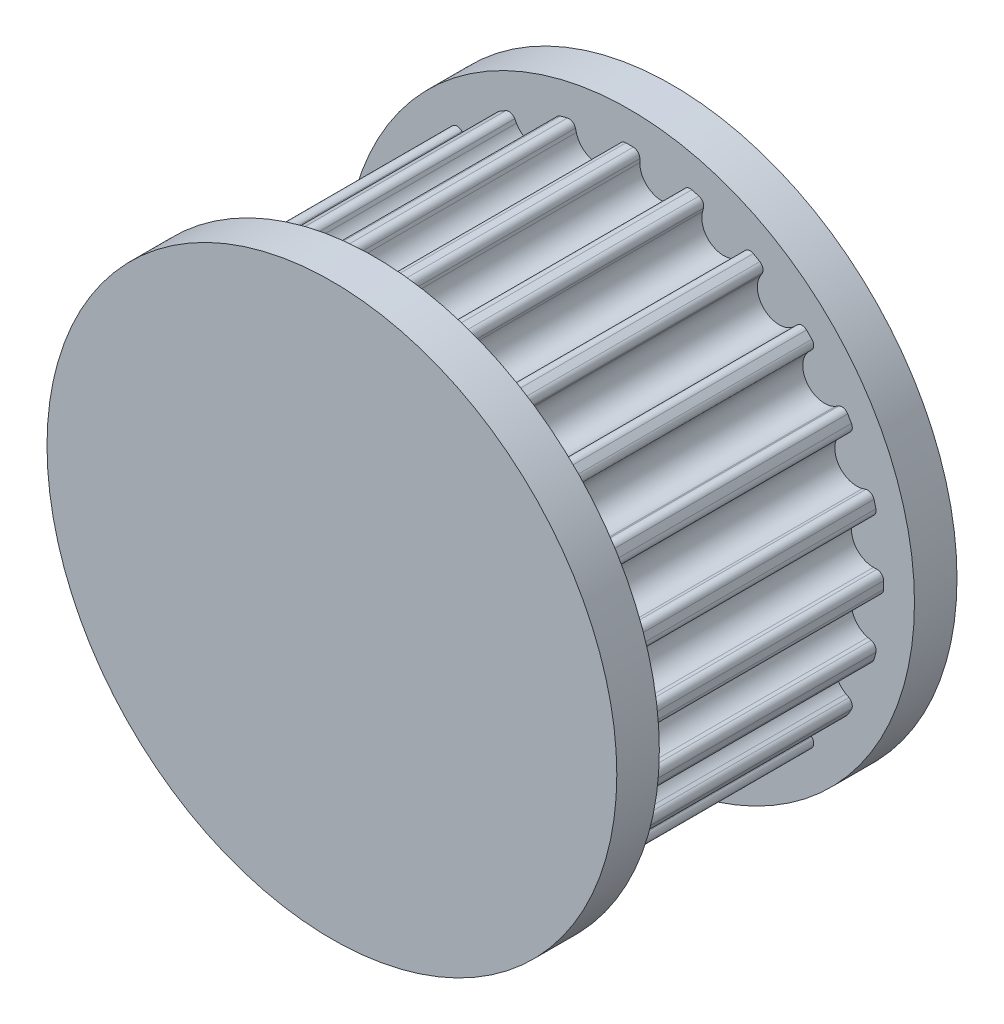
SolidWorks part; units mm, degrees
ref_plane "前视基准面" through (0, 0, 0) normal (0, 0, 1) x (1, 0, 0)
ref_plane "上视基准面" through (0, 0, 0) normal (0, 1, 0) x (1, 0, 0)
ref_plane "右视基准面" through (0, 0, 0) normal (1, 0, 0) x (0, 0, -1)
sketch "Sketch2" plane through (0, 0, 0) normal (0, 0, 1) x (1, 0, 0)
  circle A0 centre (0, 0) radius 29.875
  dimension "D1" = 59.75
extrude "Extrude1" add sketch "Sketch2" along normal blind 30
sketch "Sketch1" plane through (0, 0, 0) normal (0, 0, 1) x (1, 0, 0)
  line L0 (0, 0) -> (0, 30.56) construction
  line L1 (0, 0) -> (-3.9889, 30.2986) construction
  line L2 (-1.2065, 29.0851) -> (-1.203, 28.6801)
  line L3 (-6.3624, 28.4063) -> (-6.261, 28.0142)
  circle A0 centre (0, 0) radius 30.56 construction
  arc A1 (-0.438, 29.8718) -> (-7.3084, 28.9673) centre (0, 0) ccw
  arc A2 (-6.261, 28.0142) -> (-1.203, 28.6801) centre (-3.7729, 28.6577) ccw
  arc A3 (-0.438, 29.8718) -> (-1.2065, 29.0851) centre (-0.4265, 29.0919) ccw
  arc A4 (-7.3084, 28.9673) -> (-6.3624, 28.4063) centre (-7.1175, 28.211) cw
  point P4 (30.2986, 3.9889)
  point P5 (28.2338, 11.6948)
  point P6 (24.2449, 18.6037)
  point P7 (18.6037, 24.2449)
  point P8 (11.6948, 28.2338)
  point P9 (3.9889, 30.2986)
  point P10 (-3.9889, 30.2986)
  point P11 (-11.6948, 28.2338)
  point P12 (-18.6037, 24.2449)
  point P13 (-24.2449, 18.6037)
  point P14 (-28.2338, 11.6948)
  point P15 (-30.2986, 3.9889)
  point P16 (-30.2986, -3.9889)
  point P17 (-28.2338, -11.6948)
  point P18 (-24.2449, -18.6037)
  point P19 (-18.6037, -24.2449)
  point P20 (-11.6948, -28.2338)
  point P21 (-3.9889, -30.2986)
  point P22 (3.9889, -30.2986)
  point P23 (11.6948, -28.2338)
  point P24 (18.6037, -24.2449)
  point P25 (24.2449, -18.6037)
  point P26 (28.2338, -11.6948)
  point P27 (30.2986, -3.9889)
  dimension "D1" = 61.12
  dimension "D2" = 59.75
  dimension "D3" = 5.14
  dimension "D4" = 3.54
  dimension "D5" = 1.56
  dimension "D6" = 7
extrude "Extrude2" cut sketch "Sketch1" along normal up to surface (30 mm away) up to face at (29.875, 0, 30)
pattern_circular "CirPattern1" count 24 over 360 about axis through (0, 0, 0) along (0, 0, 1) of "Extrude2"
sketch "Sketch3" plane through (0, 0, 30) normal (0, 0, 1) x (1, 0, 0)
  circle A0 centre (0, 0) radius 33.5
  dimension "D1" = 67
extrude "Extrude3" add sketch "Sketch3" along normal blind 5
sketch "Sketch4" plane through (0, 0, 0) normal (0, 0, -1) x (-1, 0, 0)
  circle A0 centre (0, 0) radius 33.5
  circle A1 centre (0, 0) radius 33.5 construction
extrude "Extrude4" add sketch "Sketch4" along normal blind 5
ref_plane "Plane1" through (0, 0, 15) normal (0, 0, -1) x (-1, 0, 0)
sketch "Sketch6" plane through (0, 0, -5) normal (0, 0, -1) x (-1, 0, 0)
  circle A0 centre (0, 0) radius 10
  dimension "D1" = 20
extrude "Extrude5" cut sketch "Sketch6" against normal blind 30
chamfer "Chamfer1" distance 2 angle 45 1 edges at (-10, 0, -5)
